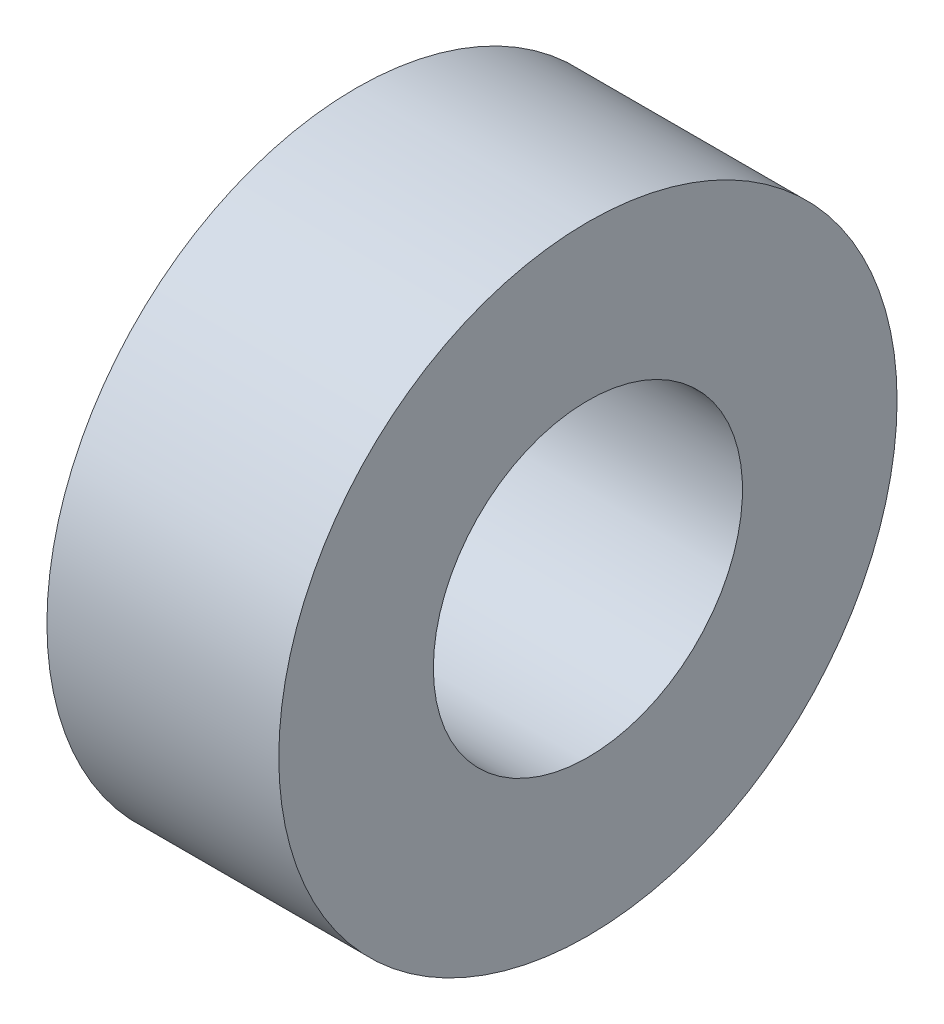
SolidWorks part; units mm, degrees
ref_plane "Front Plane" through (0, 0, 0) normal (0, 0, 1) x (1, 0, 0)
ref_plane "Top Plane" through (0, 0, 0) normal (0, 1, 0) x (1, 0, 0)
ref_plane "Right Plane" through (0, 0, 0) normal (1, 0, 0) x (0, 0, -1)
sketch "Sketch1" plane through (0, 0, 0) normal (1, 0, 0) x (0, 0, -1)
  circle A0 centre (0, 0) radius 12.7
  circle A1 centre (0, 0) radius 6.35
  dimension "D1" = 25.4
  dimension "D2" = 12.7
extrude "Boss-Extrude1" add sketch "Sketch1" along normal blind 9.525
sketch "Sketch2" plane through (9.525, 0, 0) normal (1, 0, 0) x (0, 0, -1)
  line L0 (6.35, 0) -> (12.7, 0) construction
  circle A0 centre (0, 0) radius 6.35 construction
  circle A1 centre (0, 0) radius 12.7 construction
  circle A2 centre (9.525, 0) radius 3.175
  circle A3 centre (-6.35, -10.9985) radius 3.175
  circle A4 centre (-7.9375, 8.2489) radius 3.175
  point P16 (-1.5875, -0.9165)
  dimension "D1" = 6.35
  dimension "D2" = 3
